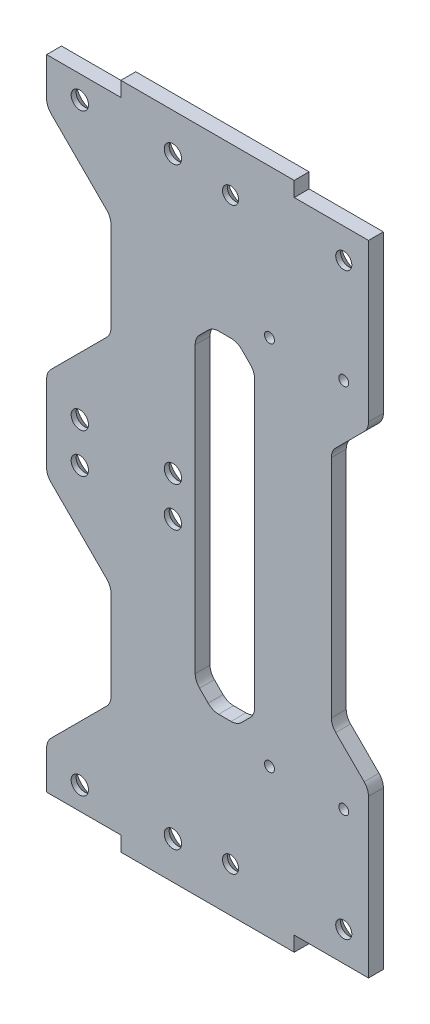
SolidWorks part; units mm, degrees
material "ABS"
ref_plane "Спереди" through (0, 0, 0) normal (0, 0, 1) x (1, 0, 0)
ref_plane "Сверху" through (0, 0, 0) normal (0, 1, 0) x (1, 0, 0)
ref_plane "Справа" through (0, 0, 0) normal (1, 0, 0) x (0, 0, -1)
sketch "Эскиз1" plane through (0, 0, 0) normal (0, 0, 1) x (1, 0, 0)
  line L0 (-32.5, 0) -> (32.5, 0) construction
  line L1 (-32.5, -64.5) -> (32.5, -64.5)
  line L2 (-32.5, -64.5) -> (-32.5, 64.5)
  line L3 (-32.5, 64.5) -> (32.5, 64.5)
  line L4 (32.5, -64.5) -> (32.5, 64.5)
  line L5 (-32.5, -64.5) -> (32.5, 64.5) construction
  line L6 (-32.5, 64.5) -> (32.5, -64.5) construction
  line L7 (-17.5, 61.5) -> (17.5, 61.5)
  line L8 (-17.5, 61.5) -> (-17.5, 67.5)
  line L9 (-17.5, 67.5) -> (17.5, 67.5)
  line L10 (17.5, 61.5) -> (17.5, 67.5)
  line L11 (-17.5, 61.5) -> (17.5, 67.5) construction
  line L12 (-17.5, 67.5) -> (17.5, 61.5) construction
  line L13 (-17.5, -67.5) -> (17.5, -61.5) construction
  line L14 (-17.5, -61.5) -> (17.5, -67.5) construction
  line L15 (17.5, -61.5) -> (17.5, -67.5)
  line L16 (-17.5, -67.5) -> (17.5, -67.5)
  line L17 (-17.5, -61.5) -> (-17.5, -67.5)
  line L18 (-17.5, -61.5) -> (17.5, -61.5)
  point P0 (0, 0)
  point P6 (0, 64.5)
  point P17 (0, -64.5)
  dimension "D1" = 3
  dimension "D2" = 35
  dimension "D3" = 15
  dimension "D4" = 129
extrude "Бобышка-Вытянуть1" add sketch "Эскиз1" along normal blind 3 contours L10 L7 L8 L3 L2 L1 L4 | L7 L10 L3 L8 | L3 L10 L9 L8 | L18 L17 L1 L15 | L1 L17 L16 L15
sketch "Эскиз2" plane through (0, 0, 3) normal (0, 0, 1) x (1, 0, 0)
  line L0 (0, 67.5) -> (0, -67.5) construction
  line L1 (-17.5, 67.5) -> (17.5, 67.5) construction
  line L3 (-32.5, 31.95) -> (32.5, 31.95) construction
  line L4 (-17.5, -67.5) -> (17.5, -67.5) construction
  line L5 (-32.5, 0) -> (32.5, 0) construction
  line L6 (-32.5, -64.5) -> (-32.5, 64.5) construction
  line L7 (-25.8, 59.9) -> (-7, 59.9) construction
  line L8 (-25.8, 59.9) -> (-25.8, 4) construction
  line L9 (-25.8, 4) -> (-7, 4) construction
  line L10 (-7, 59.9) -> (-7, 4) construction
  line L11 (-25.8, 59.9) -> (-7, 4) construction
  line L12 (-25.8, 4) -> (-7, 59.9) construction
  line L13 (32.5, -64.5) -> (32.5, 64.5) construction
  line L18 (-25.8, -4) -> (-7, -59.9) construction
  line L19 (-25.8, -59.9) -> (-7, -4) construction
  line L20 (-7, -59.9) -> (-7, -4) construction
  line L21 (-25.8, -4) -> (-7, -4) construction
  line L22 (-25.8, -59.9) -> (-25.8, -4) construction
  line L23 (-25.8, -59.9) -> (-7, -59.9) construction
  circle A0 centre (-25.8, 59.9) radius 1.75
  circle A1 centre (-7, 59.9) radius 1.75
  circle A4 centre (-25.8, 4) radius 1.75
  circle A5 centre (-7, 4) radius 1.75
  circle A8 centre (-7, -4) radius 1.75
  circle A9 centre (-25.8, -4) radius 1.75
  circle A10 centre (-7, -59.9) radius 1.75
  circle A11 centre (-25.8, -59.9) radius 1.75
  point P12 (-16.4, 31.95)
  point P31 (-16.4, -31.95)
  dimension "D4" = 3.5
  dimension "D1" = 18.8
  dimension "D2" = 55.9
  dimension "D3" = 7
  dimension "D5" = 4
extrude "Вырез-Вытянуть1" cut sketch "Эскиз2" against normal blind 10
chamfer "Фаска1" distance 2 angle 45 8 edges at (-24.05, 59.9, 0) (-5.25, 59.9, 0) (-5.25, 4, 0) (-24.05, 4, 0) (-24.05, -59.9, 0) (-5.25, -59.9, 0) (-24.05, -4, 0) (-5.25, -4, 0)
sketch "Эскиз3" plane through (0, 0, 0) normal (0, 0, -1) x (-1, 0, 0)
  line L0 (0, 67.5) -> (0, -67.5) construction
  line L1 (17.5, 67.5) -> (-17.5, 67.5) construction
  line L2 (17.5, -67.5) -> (-17.5, -67.5) construction
  line L3 (-32.5, 0) -> (32.5, 0) construction
  line L4 (-32.5, -64.5) -> (-32.5, 64.5) construction
  line L5 (32.5, -64.5) -> (32.5, 64.5) construction
  line L7 (-27.5, -37.5) -> (-12.5, -37.5) construction
  line L8 (-27.5, -37.5) -> (-27.5, 37.5) construction
  line L9 (-27.5, 37.5) -> (-12.5, 37.5) construction
  line L10 (-12.5, -37.5) -> (-12.5, 37.5) construction
  line L11 (-27.5, -37.5) -> (-12.5, 37.5) construction
  line L12 (-27.5, 37.5) -> (-12.5, -37.5) construction
  circle A0 centre (-27.5, 37.5) radius 1
  circle A1 centre (-12.5, 37.5) radius 1
  circle A2 centre (-27.5, -37.5) radius 1
  circle A3 centre (-12.5, -37.5) radius 1
  point P12 (-20, 0)
  dimension "D3" = 2
  dimension "D1" = 15
  dimension "D2" = 75
  dimension "D4" = 5
extrude "Вырез-Вытянуть2" cut sketch "Эскиз3" against normal blind 10
chamfer "Фаска2" distance 1.5 angle 45 4 edges at (26.5, -37.5, 0) (11.5, -37.5, 0) (26.5, 37.5, 0) (11.5, 37.5, 0)
sketch "Эскиз4" plane through (0, 0, 0) normal (0, 0, -1) x (-1, 0, 0)
  line L0 (0, 67.5) -> (0, -67.5) construction
  line L1 (17.5, 67.5) -> (-17.5, 67.5) construction
  line L2 (17.5, -67.5) -> (-17.5, -67.5) construction
  line L3 (-32.5, 0) -> (32.5, 0) construction
  line L4 (-32.5, -64.5) -> (-32.5, 64.5) construction
  line L5 (32.5, -64.5) -> (32.5, 64.5) construction
  line L6 (32.5, 55.5) -> (19.5, 42.5)
  line L7 (19.5, 42.5) -> (19.5, 22)
  line L8 (19.5, 22) -> (32.5, 9)
  line L9 (32.5, 55.5) -> (37.7712, 55.5)
  line L10 (37.7712, 55.5) -> (37.7712, 9)
  line L11 (37.7712, 9) -> (32.5, 9)
  line L12 (37.7712, -9) -> (32.5, -9)
  line L13 (37.7712, -55.5) -> (37.7712, -9)
  line L14 (32.5, -55.5) -> (37.7712, -55.5)
  line L15 (19.5, -22) -> (32.5, -9)
  line L16 (19.5, -42.5) -> (19.5, -22)
  line L17 (32.5, -55.5) -> (19.5, -42.5)
  dimension "D1" = 135
  dimension "D2" = 13
  dimension "D3" = 135
  dimension "D4" = 9
  dimension "D5" = 9
extrude "Вырез-Вытянуть3" cut sketch "Эскиз4" against normal blind 10
fillet "Скругление1" radius 3 8 edges at (-32.5, 9, 1.5) (-32.5, 55.5, 1.5) (-19.5, 42.5, 1.5) (-19.5, 22, 1.5) (-32.5, -9, 1.5) (-19.5, -22, 1.5) (-19.5, -42.5, 1.5) (-32.5, -55.5, 1.5)
sketch "Эскиз5" plane through (0, 0, 3) normal (0, 0, 1) x (1, 0, 0)
  line L0 (12.5, 37.5) -> (12.5, -38.5) construction
  line L1 (-7, 4) -> (-7, -4) construction
  line L2 (-7, 0) -> (12.5, 0) construction
  line L3 (1, 36.6441) -> (1, -41.2181) construction
  line L4 (1, 33.5) -> (6, 33.5)
  line L5 (9.5, 30) -> (9.5, -30)
  line L6 (6, 33.5) -> (9.5, 30)
  line L7 (6, -33.5) -> (9.5, -30)
  line L8 (1, -33.5) -> (6, -33.5)
  line L9 (1, 33.5) -> (-2.5, 30)
  line L10 (-2.5, 30) -> (-2.5, -30)
  line L11 (1, -33.5) -> (-2.5, -30)
  circle A0 centre (12.5, -37.5) radius 1 construction
  point P21 (9.5, 0)
  point P24 (6.4653, 33.5)
  point P25 (-2.5, 0)
  dimension "D1" = 135
  dimension "D2" = 12
  dimension "D3" = 135
  dimension "D4" = 3
  dimension "D5" = 4
  dimension "D6" = 5
extrude "Вырез-Вытянуть4" cut sketch "Эскиз5" against normal blind 22
fillet "Скругление2" radius 3 8 edges at (-2.5, -30, 1.5) (1, -33.5, 1.5) (6, -33.5, 1.5) (9.5, -30, 1.5) (9.5, 30, 1.5) (-2.5, 30, 1.5) (1, 33.5, 1.5) (6, 33.5, 1.5)
sketch "Эскиз6" plane through (0, 0, 0) normal (0, 0, -1) x (-1, 0, 0)
  line L0 (40.5858, 58.5) -> (-50.8933, 58.5) construction
  line L1 (-17.5, 64.5) -> (-32.5, 64.5) construction
  line L2 (-32.5, -64.5) -> (-32.5, 64.5) construction
  line L3 (-32.5, 0) -> (32.5, 0) construction
  line L4 (32.5, -7.7574) -> (32.5, 7.7574) construction
  circle A0 centre (-27.5, 58.5) radius 1.625
  circle A1 centre (-4.64, 58.5) radius 1.625
  circle A2 centre (-4.64, -58.5) radius 1.625
  circle A3 centre (-27.5, -58.5) radius 1.625
  dimension "D1" = 3.25
  dimension "D3" = 6
  dimension "D2" = 22.86
  dimension "D4" = 5
extrude "Вырез-Вытянуть5" cut sketch "Эскиз6" against normal blind 22
chamfer "Фаска3" distance 2 angle 45 4 edges at (6.265, -58.5, 0) (29.125, -58.5, 0) (3.015, 58.5, 0) (25.875, 58.5, 0)
sketch "Эскиз7" plane through (0, 0, 0) normal (0, 0, -1) x (-1, 0, 0)
  line L0 (-32.5, 31.5) -> (-25, 24)
  line L1 (-32.5, -64.5) -> (-32.5, 64.5) construction
  line L2 (-25, 24) -> (-25, -24)
  line L3 (-32.5, 0) -> (32.5, 0) construction
  line L4 (32.5, -7.7574) -> (32.5, 7.7574) construction
  line L5 (-32.5, -31.5) -> (-25, -24)
  line L6 (-32.5, 31.5) -> (-45.2784, 31.5)
  line L7 (-45.2784, 31.5) -> (-45.2784, -31.5)
  line L8 (-45.2784, -31.5) -> (-32.5, -31.5)
  circle A0 centre (-27.5, 37.5) radius 1 construction
  point P13 (-25, 0)
  dimension "D2" = 6
  dimension "D1" = 135
  dimension "D3" = 7.5
extrude "Вырез-Вытянуть6" cut sketch "Эскиз7" against normal blind 22
fillet "Скругление3" radius 3 4 edges at (32.5, -31.5, 1.5) (25, -24, 1.5) (32.5, 31.5, 1.5) (25, 24, 1.5)
